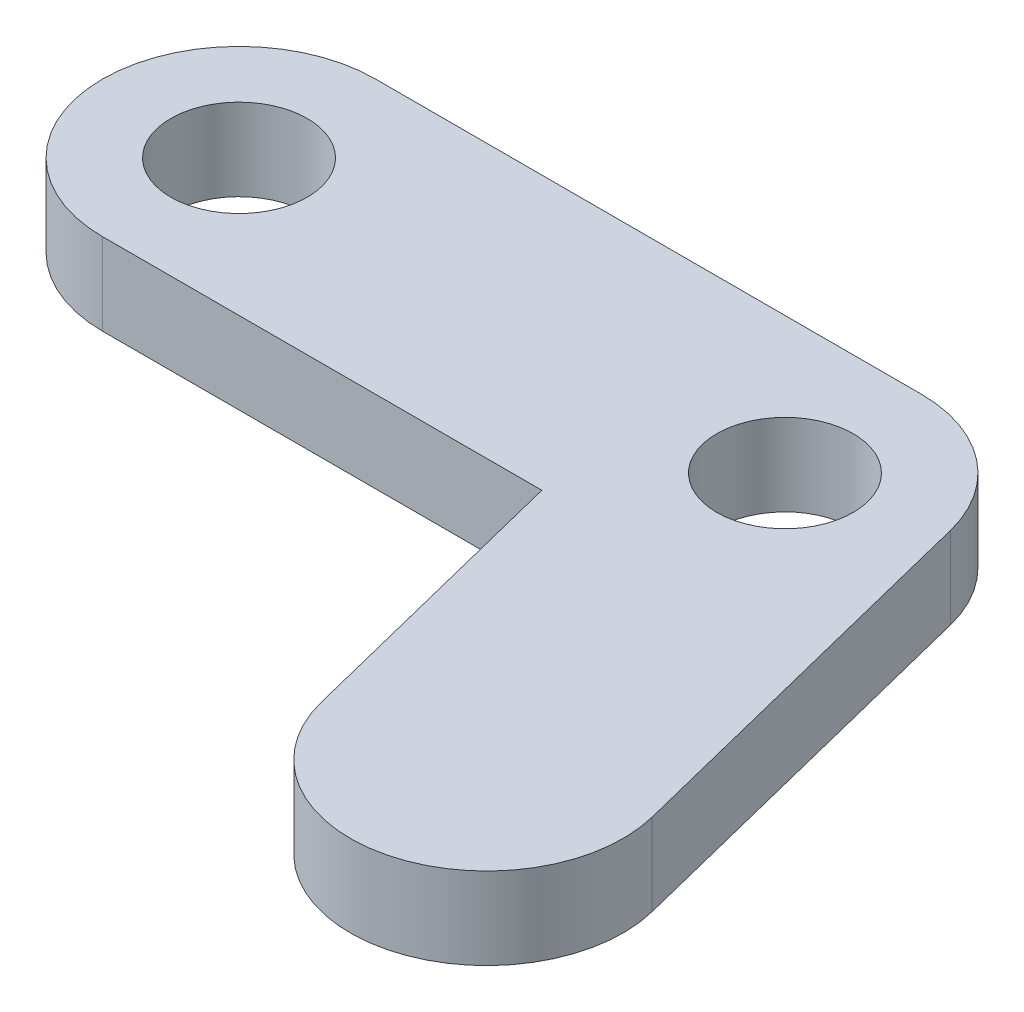
SolidWorks part; units mm, degrees
ref_plane "Front Plane" through (0, 0, 0) normal (0, 0, 1) x (1, 0, 0)
ref_plane "Top Plane" through (0, 0, 0) normal (0, 1, 0) x (1, 0, 0)
ref_plane "Right Plane" through (0, 0, 0) normal (1, 0, 0) x (0, 0, -1)
sketch "Sketch1" plane through (0, 0, 0) normal (0, 1, 0) x (1, 0, 0)
  line L0 (0, 0) -> (20, 0) construction
  line L1 (0, 5) -> (20, 5)
  line L2 (0, -5) -> (20, -5)
  line L3 (20, 0) -> (23.6288, -14.5544) construction
  line L4 (24.8515, 1.2096) -> (28.4803, -13.3448)
  line L5 (15.1485, -1.2096) -> (18.7773, -15.764)
  arc A0 (0, 5) -> (0, -5) centre (0, 0) ccw
  arc A1 (20, -5) -> (20, 5) centre (20, 0) ccw
  circle A2 centre (0, 0) radius 2.5
  circle A3 centre (20, 0) radius 2.5
  arc A4 (24.8515, 1.2096) -> (15.1485, -1.2096) centre (20, 0) ccw
  arc A5 (18.7773, -15.764) -> (28.4803, -13.3448) centre (23.6288, -14.5544) ccw
  point P3 (10, 0)
  point P12 (21.8144, -7.2772)
  dimension "D3" = 5
  dimension "D4" = 5
  dimension "D5" = 5
  dimension "D1" = 20
  dimension "D2" = 5
  dimension "D6" = 15
  dimension "D7" = 76
extrude "Boss-Extrude1" add sketch "Sketch1" along normal blind 3 contours A4 L1 A0 L2 L5 A2 | A1 A4 L5 L2 A3 | L5 A5 L4 A1 L2
